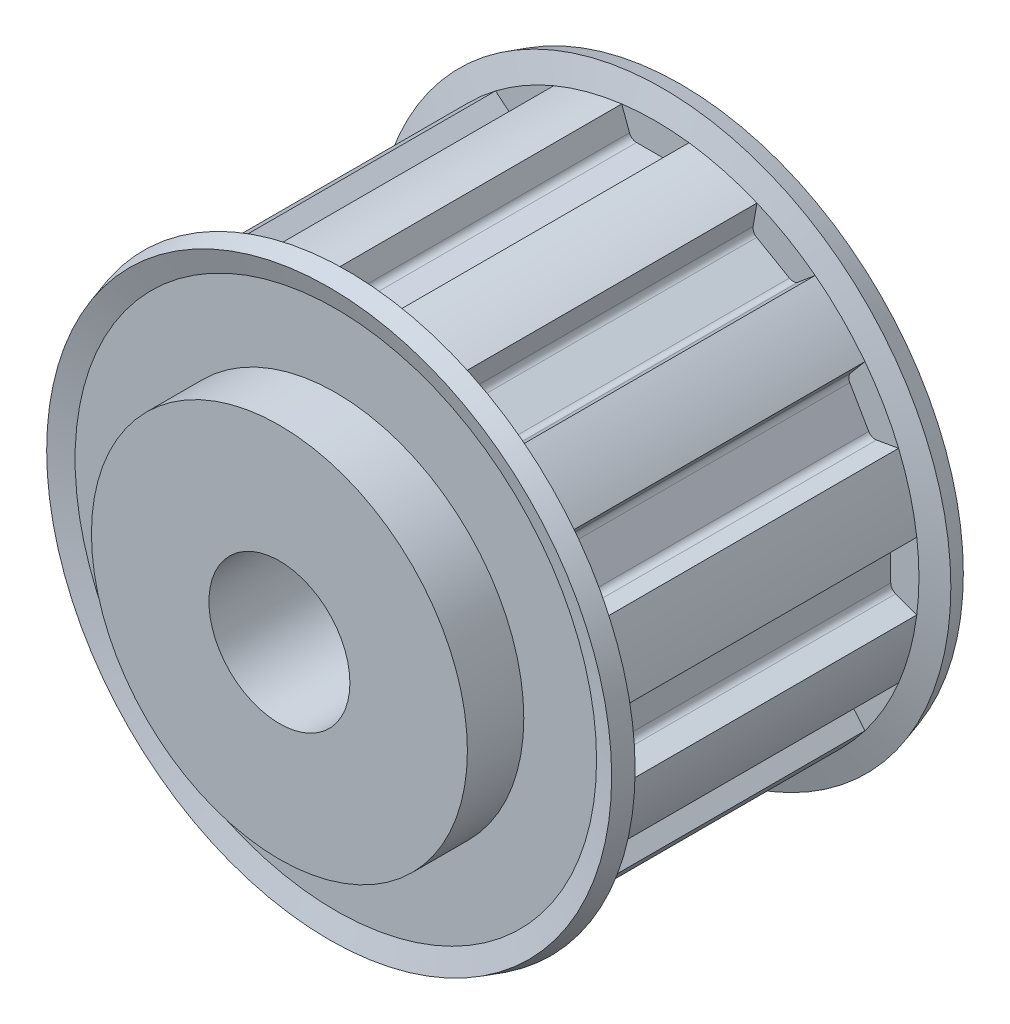
SolidWorks part; units mm, degrees
extrude "BasePulley" add sketch "Sketch1" against normal blind 20.32
sketch "Sketch1" plane through (0, 0, 0) normal (0, 0, 1) x (1, 0, 0)
  circle A0 centre (0, 0) radius 17.8054
  dimension "Outside_dia" = 35.6108
revolve "Flange" add sketch "Sketch2" angle 360 about L11
sketch "Sketch2" plane through (0, 0, 0) normal (1, 0, 0) x (0, 0, -1)
  line L0 (20.32, 17.8054) -> (20.8248, 19.4564)
  line L1 (20.8248, 19.4564) -> (22.0393, 19.0851)
  line L2 (10.16, 0) -> (10.16, 66.675) construction
  line L3 (22.0393, 19.0851) -> (21.59, 17.6156)
  line L4 (21.59, 17.6156) -> (21.59, 0)
  line L5 (0, 17.8054) -> (-0.5048, 19.4564)
  line L6 (20.32, -17.8054) -> (20.32, 17.8054) construction
  line L7 (-0.5048, 19.4564) -> (-1.7193, 19.0851)
  line L8 (-1.7193, 19.0851) -> (-1.27, 17.6156)
  line L9 (-1.27, 17.6156) -> (-1.27, 0)
  line L10 (20.32, 17.8054) -> (0, 17.8054)
  line L11 (0, 0) -> (38.2092, 0) construction
  line L12 (20.32, 0) -> (0, 0) construction
  line L13 (-1.27, 0) -> (21.59, 0)
  dimension "D1" = 10.16
  dimension "Flange_ang" = 17
  dimension "D3" = 1.27
  dimension "D2" = 17.8054
  dimension "Flange_ht" = 1.651
ref_plane "Plane1" through (0, 0, 0) normal (0, 0, 1) x (1, 0, 0)
ref_plane "Plane2" through (0, 0, 0) normal (0, 1, 0) x (1, 0, 0)
ref_plane "Plane3" through (0, 0, 0) normal (1, 0, 0) x (0, 0, -1)
sketch "Clipboard" plane through (0, 0, 0) normal (0, 0, 1) x (1, 0, 0)
  line L0 (0, 0) -> (10.7163, 0)
  line L1 (0, 0) -> (24.8449, 5.281)
  line L2 (0, 0) -> (24.8449, -5.281)
ref_plane "Plane4" through (0, 0, -10.16) normal (0, 0, 1) x (1, 0, 0)
sketch "Sketch3" plane through (0, 0, -10.16) normal (0, 0, 1) x (1, 0, 0)
  line L0 (-2.3241, 17.8054) -> (-2.3241, 43.2054)
  line L1 (2.3241, 17.8054) -> (2.3241, 43.2054)
  line L2 (0, 0) -> (0, 17.8054) construction
  line L3 (-2.3241, 17.8054) -> (2.3241, 17.8054) construction
  line L4 (-1.275, 15.9004) -> (1.275, 15.9004)
  line L5 (2.3241, 17.8054) -> (1.7524, 16.2347)
  line L6 (-2.3241, 17.8054) -> (-1.7524, 16.2347)
  line L7 (2.3241, 43.2054) -> (-2.3241, 43.2054)
  arc A0 (1.275, 15.9004) -> (1.7524, 16.2347) centre (1.275, 16.4084) ccw
  arc A2 (-1.7524, 16.2347) -> (-1.275, 15.9004) centre (-1.275, 16.4084) ccw
  dimension "Grv_rad_bot" = 0.508
  dimension "Grv_ang" = 40
  dimension "D3" = 20
  dimension "Grv_width" = 4.6482
  dimension "D4" = 25.4
  dimension "D1" = 17.8054
  dimension "Grv_depth" = 1.905
extrude "Groove" cut sketch "Sketch3" against normal mid plane 20.32
pattern_circular "Grooves" count 12 every 30 about axis through (0, 0, -20.32) along (0, 0, 1) of "Groove"
sketch "Sketch4" plane through (0, 0, 0) normal (1, 0, 0) x (0, 0, -1)
  line L0 (0, 0) -> (47.6781, 0) construction
  line L1 (20.32, 0) -> (0, 0) construction
  line L2 (0, 0) -> (-5.08, 0)
  line L3 (-5.08, 0) -> (-5.08, 12.7)
  line L4 (-5.08, 12.7) -> (0, 12.7)
  line L5 (0, 12.7) -> (0, 0)
  line L6 (-5.08, -12.7) -> (0, -12.7) construction
revolve "BaseHub" add sketch "Sketch4" angle 360 about L0
sketch "BorSke" plane through (0, 0, 5.08) normal (0, 0, 1) x (1, 0, 0)
  circle A0 centre (0, 0) radius 4.7625
extrude "Bore" cut sketch "BorSke" against normal through all
sketch "KeySke" plane through (0, 0, 5.08) normal (0, 0, 1) x (1, 0, 0)
  line L0 (1.1913, 5.9538) -> (1.1913, 0)
  line L1 (1.1913, 5.9538) -> (-1.1913, 5.9538)
  line L2 (-1.1913, 5.9538) -> (-1.1913, 0)
  line L3 (-1.1913, 0) -> (1.1913, 0)
  line L4 (0, 31.75) -> (0, -3.175) construction
extrude "Keyway" [suppressed] cut sketch "KeySke" against normal through all
pattern_circular "Keyway2" [suppressed] count 2 every 90
equation "\"D1@Plane4\" = \"Width@BasePulley\" / 2"
equation "\"D1@Groove\" = \"Width@BasePulley\""
equation "\"D1@Sketch3\" = \"Outside_dia@Sketch1\" / 2"
equation "\"D1@Sketch2\" = \"Width@BasePulley\" / 2"
equation "\"D2@Sketch2\" = \"Outside_dia@Sketch1\" / 2"
equation "\"D3@Sketch2\" = \"Flange_thickness@Sketch2\""
equation "\"Num_grvs@Clipboard\" = int( \"Num_grvs@Clipboard\" )"
equation "\"Show_grvs@Clipboard\" = int( \"Show_grvs@Clipboard\" )"
equation "\"Show_grvs@Clipboard\" = ((sgn( \"Show_grvs@Clipboard\" - \"Num_grvs@Clipboard\" )-1)*( \"Show_grvs@Clipboard\" - \"Num_grvs@Clipboard\" ))/-2+ \"Num_grvs@Clipboard\""
equation "\"Show_grvs@Clipboard\" = ((sgn( \"Show_grvs@Clipboard\" - 1.0)+1)*( \"Show_grvs@Clipboard\" - 1.0))/2 +1.0"
equation "\"Angle@Grooves\" = 360.0 / \"Num_grvs@Clipboard\""
equation "\"Num_grvs@Grooves\" =  \"Show_grvs@Clipboard\""
equation "\"Offset@KeySke\" = \"T_dim@Clipboard\" - \"Diameter@BorSke\" / 2.0"
equation "\"OAL@Clipboard\" = \"Overall_len@Clipboard\""
equation "\"Hub_depth@Sketch4\" = \"OAL@Clipboard\" - \"Width@BasePulley\""
